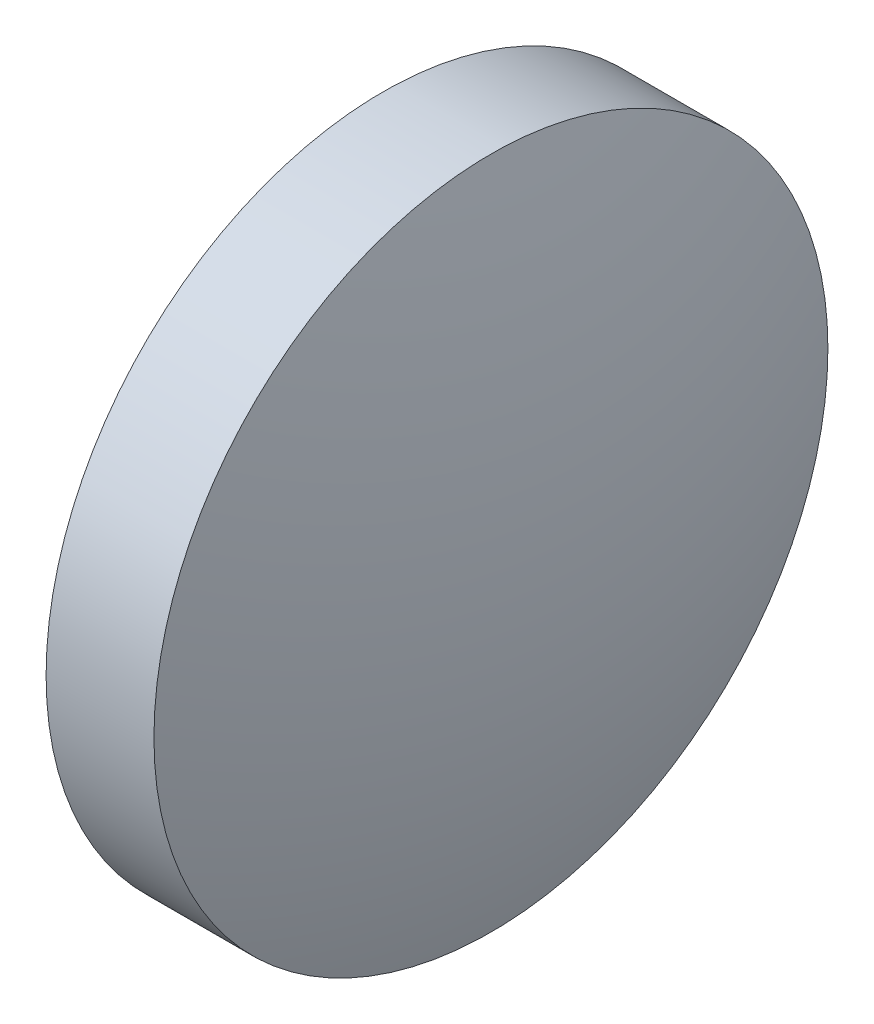
SolidWorks part; units mm, degrees
ref_plane "Plan de face" through (0, 0, 0) normal (0, 0, 1) x (1, 0, 0)
ref_plane "Plan de dessus" through (0, 0, 0) normal (0, 1, 0) x (1, 0, 0)
ref_plane "Plan de droite" through (0, 0, 0) normal (1, 0, 0) x (0, 0, -1)
ref_plane "Plan3" through (0, 10, 0) normal (0, 1, 0) x (-1, 0, 0)
sketch "Esquisse11" plane through (0, 0, 0) normal (0, 1, 0) x (1, 0, 0)
  line L0 (0, 0) -> (-35.5294, 0) construction
  line L1 (0, 0) -> (0, -23.625) construction
  line L2 (2, -12.5) -> (-2, -12.5)
  line L3 (-4.0033, 0) -> (4.0033, 0)
  arc A0 (-2, -12.5) -> (-4.0033, 0) centre (35.9967, 0) cw
  arc A1 (2, -12.5) -> (4.0033, 0) centre (-35.9967, 0) ccw
  point P11 (0, -12.5)
  dimension "D2" = 40
  dimension "D1" = 25
  dimension "D3" = 2
revolve "Révolution3" add sketch "Esquisse11" angle 360 about L0
